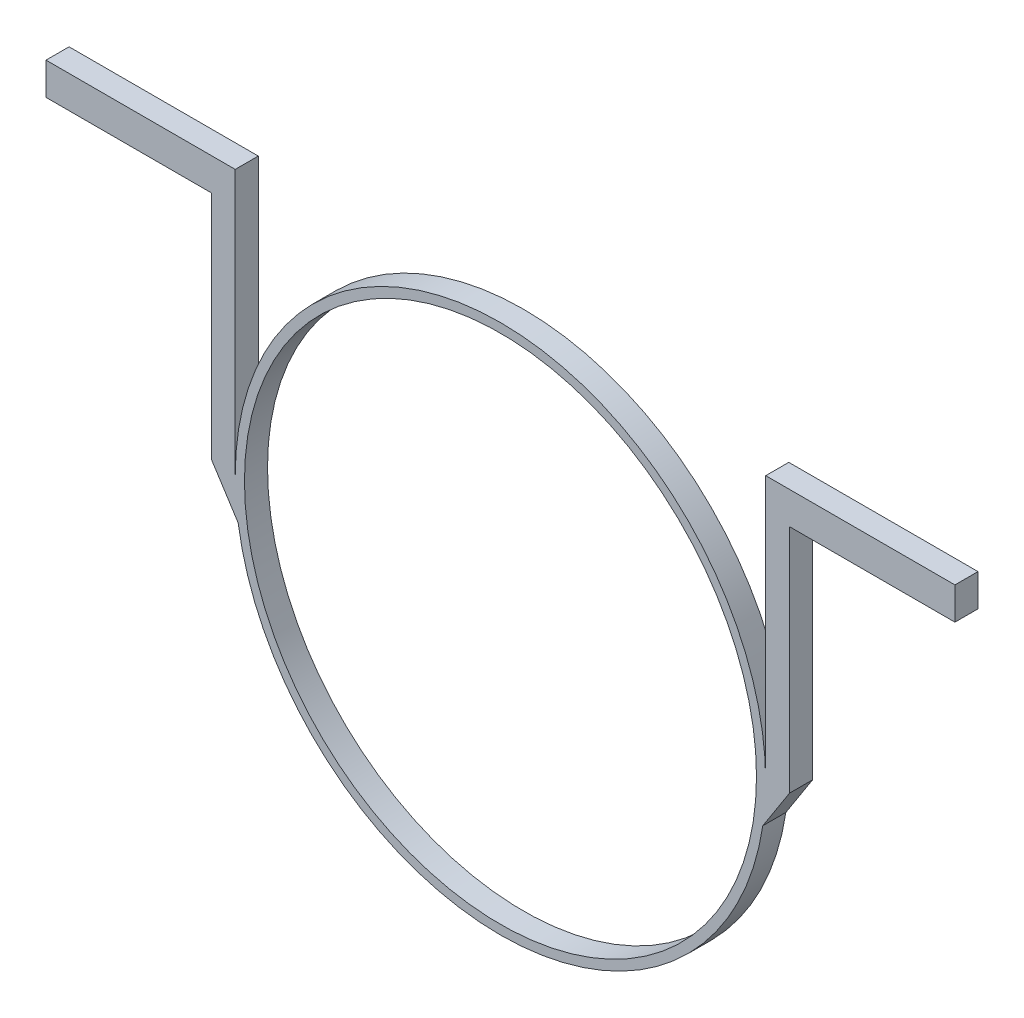
SolidWorks part; units mm, degrees
ref_plane "Ön Düzlem" through (0, 0, 0) normal (0, 0, 1) x (1, 0, 0)
ref_plane "Üst Düzlem" through (0, 0, 0) normal (0, 1, 0) x (1, 0, 0)
ref_plane "Sağ Düzlem" through (0, 0, 0) normal (1, 0, 0) x (0, 0, -1)
sketch "Sketch1" plane through (0, 0, 0) normal (0, 0, 1) x (1, 0, 0)
  line L0 (-57.5, 0) -> (-57.5, 57.5)
  line L1 (-57.5, 57.5) -> (-98.5181, 57.5)
  line L2 (-98.5181, 57.5) -> (-98.5181, 50.5)
  line L3 (-98.5181, 50.5) -> (-62.6628, 50.5)
  line L4 (-62.6628, 50.5) -> (-62.6628, 0.4745)
  line L5 (-62.6628, 0.4745) -> (-56.8605, -8.5516)
  line L6 (0, 0) -> (0, 38.8454) construction
  line L7 (57.5, 0) -> (57.5, 57.5)
  line L8 (62.6628, 0.4745) -> (56.8605, -8.5516)
  line L9 (62.6628, 50.5) -> (62.6628, 0.4745)
  line L10 (98.5181, 50.5) -> (62.6628, 50.5)
  line L11 (98.5181, 57.5) -> (98.5181, 50.5)
  line L12 (57.5, 57.5) -> (98.5181, 57.5)
  circle A0 centre (0, 0) radius 55.5
  circle A1 centre (0, 0) radius 57.5
  dimension "D1" = 111
  dimension "D3" = 7
  dimension "D4" = 50.0255
  dimension "D2" = 2
extrude "Boss-Extrude1" add sketch "Sketch1" along normal blind 5 contours A1 L0 L1 L2 L3 L4 L5 | A1 A0 | A1 L8 L9 L10 L11 L12 L7
